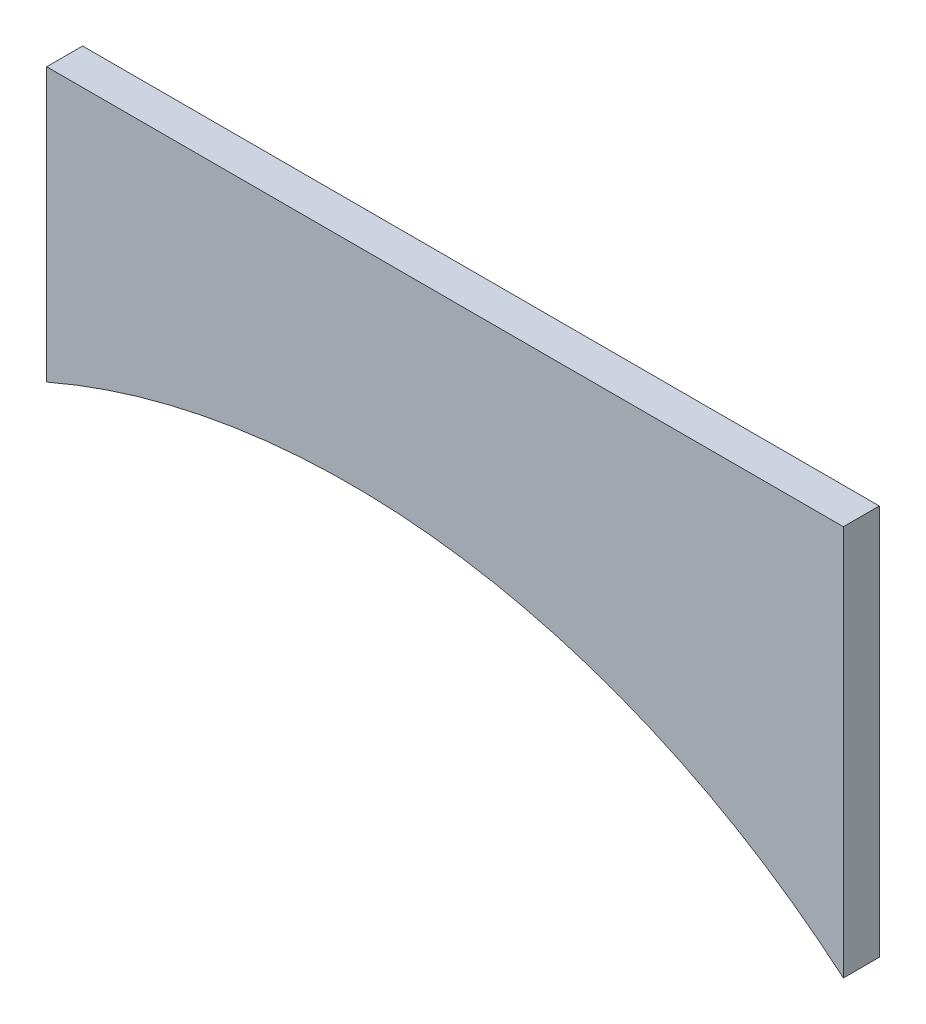
SolidWorks part; units mm, degrees
ref_plane "Front Plane" through (0, 0, 0) normal (0, 0, 1) x (1, 0, 0)
ref_plane "Top Plane" through (0, 0, 0) normal (0, 1, 0) x (1, 0, 0)
ref_plane "Right Plane" through (0, 0, 0) normal (1, 0, 0) x (0, 0, -1)
sketch "Sketch1" plane through (0, 0, 0) normal (0, 0, 1) x (1, 0, 0)
  line L1 (0, 0) -> (66.548, 0)
  line L2 (0, 0) -> (0, 45.72)
  line L3 (0, 45.72) -> (66.548, 45.72)
  line L4 (66.548, 0) -> (66.548, 45.72)
  dimension "D1" = 66.548
  dimension "D2" = 45.72
extrude "Boss-Extrude1" add sketch "Sketch1" along normal blind 3
sketch "Sketch2" plane through (0, 0, 3) normal (0, 0, 1) x (1, 0, 0)
  line L0 (0, 45.72) -> (0, 0) construction
  line L1 (0, 0) -> (66.548, 0) construction
  circle A0 centre (25.4, -35.29) radius 63.5
  dimension "D1" = 127
  dimension "D2" = 25.4
  dimension "D3" = 35.29
extrude "Cut-Extrude1" cut sketch "Sketch2" against normal through all
